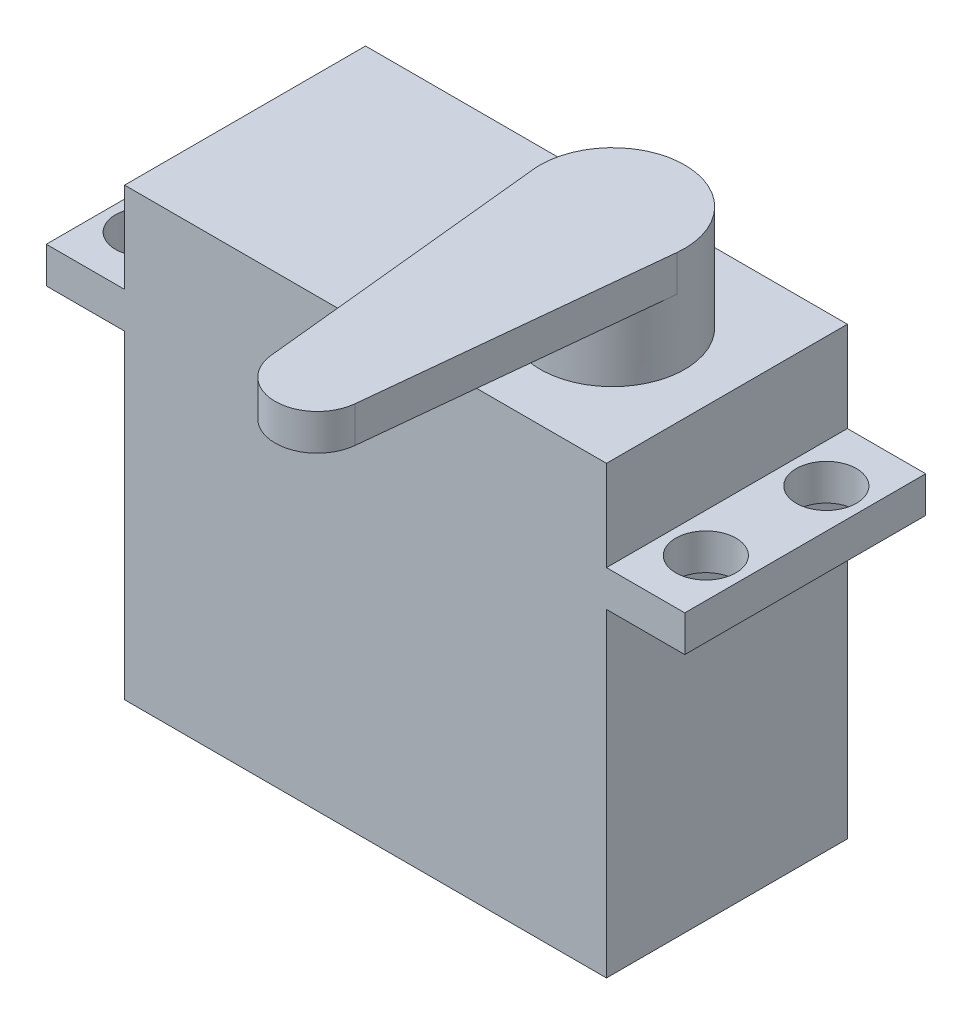
SolidWorks part; units mm, degrees
ref_plane "Front Plane" through (0, 0, 0) normal (0, 0, 1) x (1, 0, 0)
ref_plane "Top Plane" through (0, 0, 0) normal (0, 1, 0) x (1, 0, 0)
ref_plane "Right Plane" through (0, 0, 0) normal (1, 0, 0) x (0, 0, -1)
sketch "Sketch1" plane through (0, 0, 0) normal (0, 0, 1) x (1, 0, 0)
  line L0 (0, 0) -> (0, -37)
  line L1 (40, -37) -> (40, 0)
  line L2 (40, 0) -> (0, 0)
  line L3 (0, -37) -> (40, -37)
  dimension "D1" = 37
  dimension "D2" = 40
extrude "Boss-Extrude1" add sketch "Sketch1" along normal blind 20
sketch "Sketch2" plane through (0, 0, 20) normal (0, 0, 1) x (1, 0, 0)
  line L0 (0, -7.5) -> (0, -10.5)
  line L1 (0, 0) -> (0, -37) construction
  line L2 (0, -10.5) -> (-6.5, -10.5)
  line L3 (-6.5, -10.5) -> (-6.5, -7.5)
  line L4 (0, -7.5) -> (-6.5, -7.5)
  line L5 (0, -37) -> (40, -37) construction
  line L6 (20, 0) -> (20, -37)
  line L7 (40, 0) -> (0, 0) construction
  line L8 (40, -7.5) -> (40, -10.5)
  line L9 (40, -10.5) -> (46.5, -10.5)
  line L10 (46.5, -10.5) -> (46.5, -7.5)
  line L11 (40, -7.5) -> (46.5, -7.5)
  line M7 (0, 0) -> (0, -37)
  line M9 (40, -37) -> (40, 0)
  dimension "D1" = 26.5
  dimension "D2" = 3
  dimension "D3" = 3
  dimension "D4" = 6.5
extrude "Boss-Extrude2" add sketch "Sketch2" against normal blind 20 contours L4 L3 L2 M7 | L11 L9 L10 M9
ref_plane "Plane1" through (0, 8.7, 0) normal (0, 1, 0) x (1, 0, 0)
sketch "Sketch3" plane through (0, 8.7, 0) normal (0, 1, 0) x (1, 0, 0)
  line L0 (40, -10) -> (0, -10)
  line L1 (40, 0) -> (40, -20) construction
  line L2 (0, 0) -> (0, -20) construction
  circle A0 centre (30.5, -10) radius 6
  dimension "D2" = 12
  dimension "D1" = 9.5
extrude "Boss-Extrude3" add sketch "Sketch3" against normal blind 8.7 contours L0 A0 | L0 A0
sketch "Sketch4" plane through (0, 8.7, 0) normal (0, 1, 0) x (1, 0, 0)
  line L0 (30.5, -10) -> (30.5, -34.5)
  line L2 (36.4687, -10.6122) -> (33.9817, -34.8571)
  line L3 (24.5313, -10.6122) -> (27.0183, -34.8571)
  arc A0 (27.0183, -34.8571) -> (33.9817, -34.8571) centre (30.5, -34.5) ccw
  circle A2 centre (30.5, -10) radius 6 construction
  circle A3 centre (30.5, -10) radius 6 construction
  arc A4 (36.4687, -10.6122) -> (24.5313, -10.6122) centre (30.5, -10) ccw
  point P1 (0, 0)
  dimension "D2" = 7
  dimension "D3" = 24.5
extrude "Boss-Extrude4" add sketch "Sketch4" against normal blind 3
sketch "Sketch5" plane through (0, -10.5, 0) normal (0, -1, 0) x (1, 0, 0)
  line L0 (40, 20) -> (46.5, 20) construction
  line L1 (40, 0) -> (46.5, 0) construction
  line L2 (43.25, 20) -> (43.25, 0) construction
  line L3 (-3.25, 20) -> (-3.25, 0) construction
  line L4 (0, 20) -> (-6.5, 20) construction
  line L5 (0, 0) -> (-6.5, 0) construction
  circle A0 centre (43.25, 15) radius 2.5
  circle A1 centre (43.25, 5) radius 2.5
  circle A2 centre (-3.25, 15) radius 2.5
  circle A3 centre (-3.25, 5) radius 2.5
  point P20 (-13.1551, 16.9551)
  point P21 (0, 0)
  point P22 (0, 0)
  dimension "D3" = 5
  dimension "D1" = 5
  dimension "D2" = 5
  dimension "D4" = 5
  dimension "D5" = 5
extrude "Cut-Extrude2" cut sketch "Sketch5" against normal up to next
sketch "Sketch9" plane through (0, 0, 0) normal (0, 1, 0) x (1, 0, 0)
